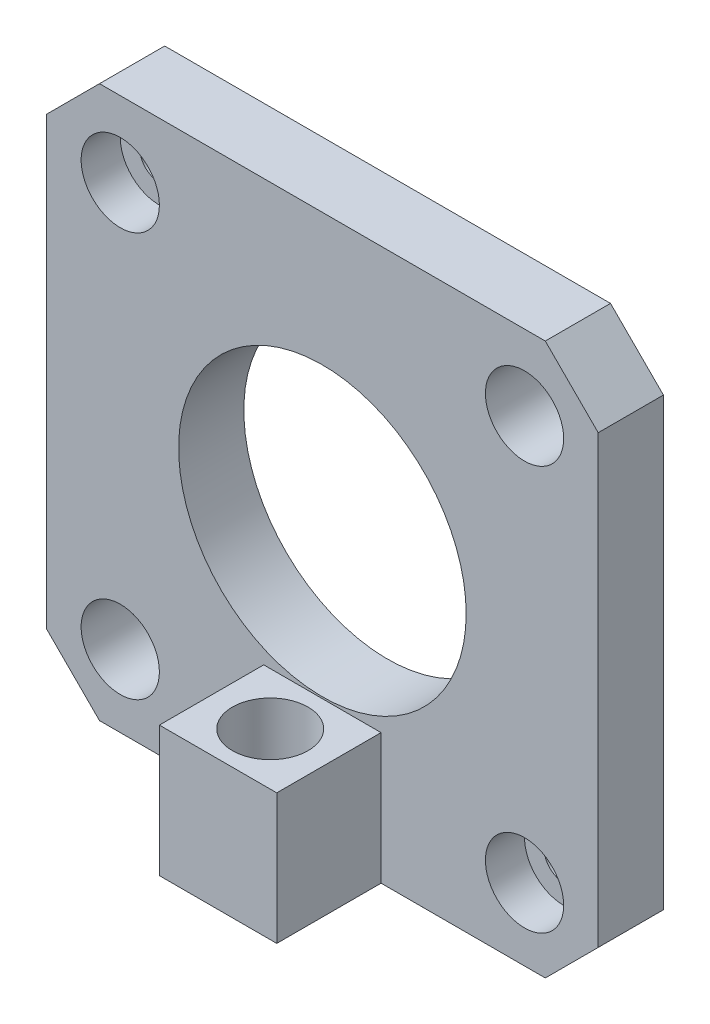
SolidWorks part; units mm, degrees
ref_plane "Front Plane" through (0, 0, 0) normal (0, 0, 1) x (1, 0, 0)
ref_plane "Top Plane" through (0, 0, 0) normal (0, 1, 0) x (1, 0, 0)
ref_plane "Right Plane" through (0, 0, 0) normal (1, 0, 0) x (0, 0, -1)
sketch "Sketch1" plane through (0, 0, 0) normal (0, 0, 1) x (1, 0, 0)
  line L0 (-21150, 17212.9994) -> (-17091.7811, 21271.2183)
  line L1 (-17091.7811, -21028.7817) -> (17091.7811, -21028.7817)
  line L2 (-21150, -16970.5627) -> (-21150, 17212.9994)
  line L3 (-17091.7811, 21271.2183) -> (17091.7811, 21271.2183)
  line L4 (21150, -16970.5627) -> (21150, 17212.9994)
  line L5 (-29910.6168, -90.9137) -> (30333.0875, 92.1978) construction
  line L6 (0, 29819.7031) -> (0, -29577.2665) construction
  line L7 (17091.7811, 21271.2183) -> (21150, 17212.9994)
  line L8 (17091.7811, -21028.7817) -> (21150, -16970.5627)
  line L9 (-17091.7811, -21028.7817) -> (-21150, -16970.5627)
  arc A0 (-17091.7811, -21028.7817) -> (17091.7811, -21028.7817) centre (0, 121.2183) ccw construction
  arc A1 (21150, -16970.5627) -> (21150, 17212.9994) centre (0, 121.2183) ccw construction
  arc A2 (17091.7811, 21271.2183) -> (-17091.7811, 21271.2183) centre (0, 121.2183) ccw construction
  arc A3 (-21150, 17212.9994) -> (-21150, -16970.5627) centre (0, 121.2183) ccw construction
  circle A4 centre (0, 121.2183) radius 11025
  point P0 (0, 0)
  dimension "D2" = 42300
  dimension "D3" = 22050
  dimension "D1" = 42300
extrude "Boss-Extrude1" add sketch "Sketch1" along normal blind 5000
sketch "Sketch2" plane through (0, 0, 5000) normal (0, 0, 1) x (1, 0, 0)
  line L0 (0, -21028.7817) -> (0, -11028.7817) construction
  line L1 (-17091.7811, -21028.7817) -> (17091.7811, -21028.7817) construction
  line L2 (0, -11028.7817) -> (4500, -11028.7817)
  line L3 (4500, -11028.7817) -> (4500, -21028.7817)
  line L4 (4500, -21028.7817) -> (-4500, -21028.7817)
  line L5 (-4500, -21028.7817) -> (-4500, -11028.7817)
  line L6 (-4500, -11028.7817) -> (0, -11028.7817)
  dimension "D1" = 9000
extrude "Boss-Extrude2" add sketch "Sketch2" along normal blind 8000
sketch "Sketch4" plane through (0, 0, 5000) normal (0, 0, 1) x (1, 0, 0)
  line L1 (-15500, -15500) -> (15500, -15500) construction
  line L2 (-15500, -15500) -> (-15500, 15500) construction
  line L3 (-15500, 15500) -> (15500, 15500) construction
  line L4 (15500, -15500) -> (15500, 15500) construction
  line L5 (-15500, -15500) -> (15500, 15500) construction
  line L6 (-15500, 15500) -> (15500, -15500) construction
  circle A0 centre (-15500, 15500) radius 3000
  circle A1 centre (15500, 15500) radius 3000
  circle A2 centre (15500, -15500) radius 3000
  circle A3 centre (-15500, -15500) radius 3000
  point P0 (0, 0)
  dimension "D1" = 6000
  dimension "D2" = 31000
  dimension "D3" = 31000
extrude "Cut-Extrude2" cut sketch "Sketch4" against normal blind 3000
sketch "Sketch5" plane through (0, 0, 2000) normal (0, 0, 1) x (1, 0, 0)
  circle A0 centre (-15500, 15500) radius 1500
  circle A1 centre (15500, -15500) radius 1500
extrude "Cut-Extrude3" cut sketch "Sketch5" against normal blind 3000
sketch "Sketch6" plane through (0, 0, 2000) normal (0, 0, 1) x (1, 0, 0)
  circle A1 centre (15500, 15500) radius 3000
  circle A2 centre (15500, 15500) radius 3000
  circle A3 centre (-15500, -15500) radius 3000
  circle A4 centre (-15500, -15500) radius 3000
  dimension "D1" = 0
  dimension "D2" = 0
extrude "Cut-Extrude4" cut sketch "Sketch6" against normal blind 3000
sketch "Sketch3" plane through (0, -21028.7817, 0) normal (0, -1, 0) x (1, 0, 0)
  line L0 (-4500, 5000) -> (4500, 13000) construction
  line L1 (-4500, 13000) -> (4500, 5000) construction
  circle A0 centre (0, 9000) radius 2900
extrude "Cut-Extrude1" cut sketch "Sketch3" against normal blind 12018
scale "Scale6" scale about centroid uniform scaling yes scale factor 0.001
